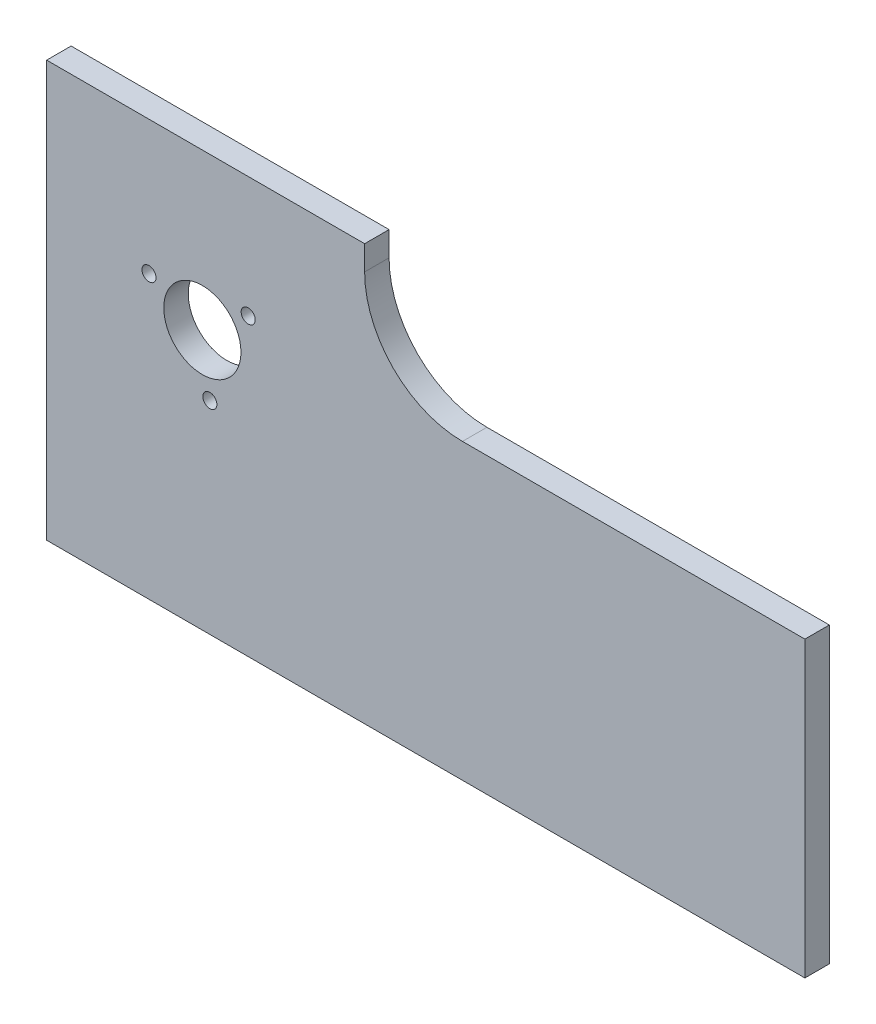
SolidWorks part; units mm, degrees
ref_plane "Front Plane" through (0, 0, 0) normal (0, 0, 1) x (1, 0, 0)
ref_plane "Top Plane" through (0, 0, 0) normal (0, 1, 0) x (1, 0, 0)
ref_plane "Right Plane" through (0, 0, 0) normal (1, 0, 0) x (0, 0, -1)
sketch "Sketch2" plane through (0, 0, 0) normal (0, 0, 1) x (1, 0, 0)
  line L0 (-82.55, -6.35) -> (-82.55, 101.6)
  line L1 (-82.55, 101.6) -> (0, 101.6)
  line L2 (25.4, 69.85) -> (114.3, 69.85)
  line L3 (114.3, 69.85) -> (114.3, -6.35)
  line L4 (114.3, -6.35) -> (-82.55, -6.35)
  line L5 (0, 95.25) -> (0, 101.6)
  arc A0 (0, 95.25) -> (25.4, 69.85) centre (25.4, 95.25) ccw construction
  arc A1 (0, 95.25) -> (25.4, 69.85) centre (25.4, 95.25) ccw
extrude "Boss-Extrude1" add sketch "Sketch2" along normal blind 6.35
sketch "Sketch4" plane through (0, 0, 6.35) normal (0, 0, 1) x (1, 0, 0)
  circle A0 centre (-42.1287, 61.1227) radius 10.0203 construction
  circle A1 centre (-30.2247, 70.2494) radius 1.8288 construction
  circle A2 centre (-55.9846, 66.8684) radius 1.8288 construction
  circle A3 centre (-40.1767, 46.2502) radius 1.8288 construction
  circle A4 centre (-42.1287, 61.1227) radius 10.0203
  circle A5 centre (-30.2247, 70.2494) radius 1.8288
  circle A6 centre (-55.9846, 66.8684) radius 1.8288
  circle A7 centre (-40.1767, 46.2502) radius 1.8288
extrude "Cut-Extrude3" cut sketch "Sketch4" against normal through all
